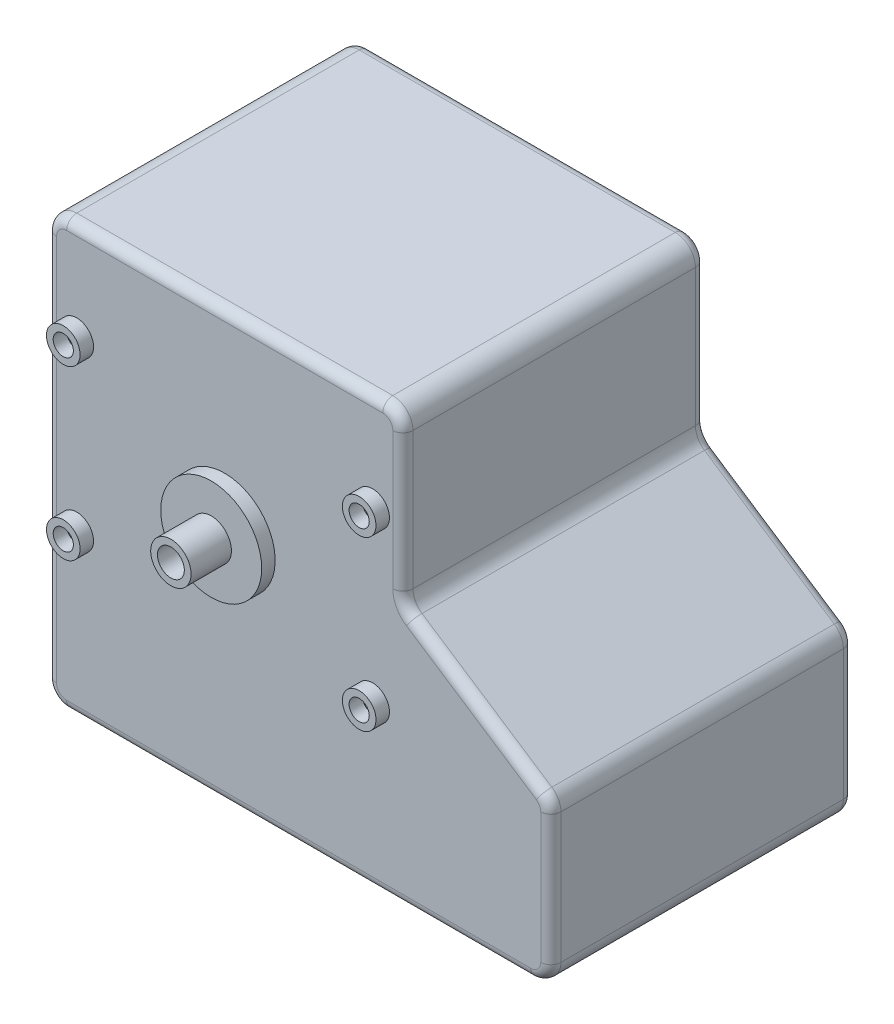
SolidWorks part; units mm, degrees
ref_plane "Front Plane" through (0, 0, 0) normal (0, 0, 1) x (1, 0, 0)
ref_plane "Top Plane" through (0, 0, 0) normal (0, 1, 0) x (1, 0, 0)
ref_plane "Right Plane" through (0, 0, 0) normal (1, 0, 0) x (0, 0, -1)
sketch "Sketch2" plane through (0, 0, 0) normal (0, 0, 1) x (1, 0, 0)
  line L0 (26.5, 6.75) -> (48.5, -7.75)
  line L1 (-26.5, -31.75) -> (26.5, -31.75)
  line L2 (-26.5, -31.75) -> (-26.5, 31.75)
  line L3 (-26.5, 31.75) -> (26.5, 31.75)
  line L4 (26.5, 6.75) -> (26.5, 31.75)
  line L5 (-26.5, -31.75) -> (26.5, 31.75) construction
  line L6 (-26.5, 31.75) -> (26.5, -31.75) construction
  line L7 (48.5, -7.75) -> (48.5, -31.75)
  line L8 (48.5, -31.75) -> (26.5, -31.75)
  line L9 (55, 0) -> (-55, 0) construction
  point P0 (0, 0)
  dimension "D1" = 63.5
  dimension "D2" = 53
  dimension "D3" = 75
  dimension "D4" = 24
  dimension "D5" = 31.75
  dimension "D6" = 25
extrude "Boss-Extrude1" add sketch "Sketch2" along normal mid plane 45
sketch "Sketch3" plane through (0, 0, 22.5) normal (0, 0, 1) x (1, 0, 0)
  line L0 (0, -24.75) -> (0, 24.75) construction
  line L1 (-22, -7.75) -> (22, -7.75) construction
  line L2 (-22, -7.75) -> (-22, 17.25) construction
  line L3 (-22, 17.25) -> (22, 17.25) construction
  line L4 (22, -7.75) -> (22, 17.25) construction
  line L5 (-22, -7.75) -> (22, 17.25) construction
  line L6 (-22, 17.25) -> (22, -7.75) construction
  line L7 (-26.5, -31.75) -> (48.5, -31.75) construction
  circle A0 centre (-22, 17.25) radius 1.5
  circle A1 centre (-22, -7.75) radius 1.5
  circle A2 centre (22, -7.75) radius 1.5
  circle A3 centre (22, 17.25) radius 1.5
  circle A4 centre (-22, 17.25) radius 2.5
  circle A5 centre (22, 17.25) radius 2.5
  circle A6 centre (-22, -7.75) radius 2.5
  circle A7 centre (22, -7.75) radius 2.5
  point P0 (0, 4.75)
  dimension "D4" = 3
  dimension "D5" = 5
  dimension "D1" = 36.5
  dimension "D2" = 44
  dimension "D3" = 25
extrude "Boss-Extrude2" add sketch "Sketch3" along normal blind 2
sketch "Sketch5" plane through (0, 0, 22.5) normal (0, 0, 1) x (1, 0, 0)
  line L0 (0, -24.75) -> (0, 24.75) construction
  line L1 (-26.5, -31.75) -> (48.5, -31.75) construction
  circle A0 centre (0, 3.25) radius 7.5
  dimension "D1" = 15
  dimension "D2" = 35
extrude "Boss-Extrude4" add sketch "Sketch5" along normal blind 2
fillet "Fillet1" radius 3 6 edges at (-26.5, -31.75, 0) (-26.5, 31.75, 0) (48.5, -31.75, 0) (48.5, -7.75, 0) (26.5, 6.75, 0) (26.5, 31.75, 0)
fillet "Fillet2" radius 1.5 24 edges at (26.8587, 6.9432, -22.5) (37.5, -0.5, -22.5) (48.1413, -7.9432, -22.5) (48.5, -19.0579, -22.5) (47.6213, -30.8713, -22.5) (11, -31.75, -22.5) (-25.6213, -30.8713, -22.5) (-26.5, 0, -22.5) (-25.6213, 30.8713, -22.5) (0, 31.75, -22.5) (25.6213, 30.8713, -22.5) (25.6213, 30.8713, 22.5) (26.5, 18.5579, 22.5) (26.8587, 6.9432, 22.5) (37.5, -0.5, 22.5) (48.1413, -7.9432, 22.5) (48.5, -19.0579, 22.5) (47.6213, -30.8713, 22.5) (11, -31.75, 22.5) (-25.6213, -30.8713, 22.5) (-26.5, 0, 22.5) (-25.6213, 30.8713, 22.5) (26.5, 18.5579, -22.5) (0, 31.75, 22.5)
sketch "Sketch7" plane through (0, 0, 24.5) normal (0, 0, 1) x (1, 0, 0)
  circle A0 centre (0, 3.25) radius 3
  dimension "D1" = 6
extrude "Boss-Extrude6" add sketch "Sketch7" along normal blind 6
sketch "Sketch8" plane through (0, 0, 30.5) normal (0, 0, 1) x (1, 0, 0)
  circle A0 centre (0, 3.25) radius 2
  dimension "D1" = 4
extrude "Cut-Extrude2" cut sketch "Sketch8" against normal through all
sketch "Sketch9" plane through (0, 0, -22.5) normal (0, 0, -1) x (-1, 0, 0)
  line L1 (-7.5, -9.25) -> (7.5, -9.25)
  line L2 (-12.5, -4.25) -> (-12.5, 10.75)
  line L3 (-7.5, 15.75) -> (7.5, 15.75)
  line L4 (12.5, -4.25) -> (12.5, 10.75)
  line L5 (-12.5, -9.25) -> (12.5, 15.75) construction
  line L6 (-12.5, 15.75) -> (12.5, -9.25) construction
  arc A0 (7.5, -9.25) -> (12.5, -4.25) centre (7.5, -4.25) ccw
  arc A1 (-7.5, -9.25) -> (-12.5, -4.25) centre (-7.5, -4.25) cw
  arc A2 (-12.5, 10.75) -> (-7.5, 15.75) centre (-7.5, 10.75) cw
  arc A3 (7.5, 15.75) -> (12.5, 10.75) centre (7.5, 10.75) cw
  point P0 (0, 3.25)
  dimension "D3" = 5
  dimension "D1" = 25
  dimension "D2" = 25
extrude "Boss-Extrude7" add sketch "Sketch9" along normal blind 8
